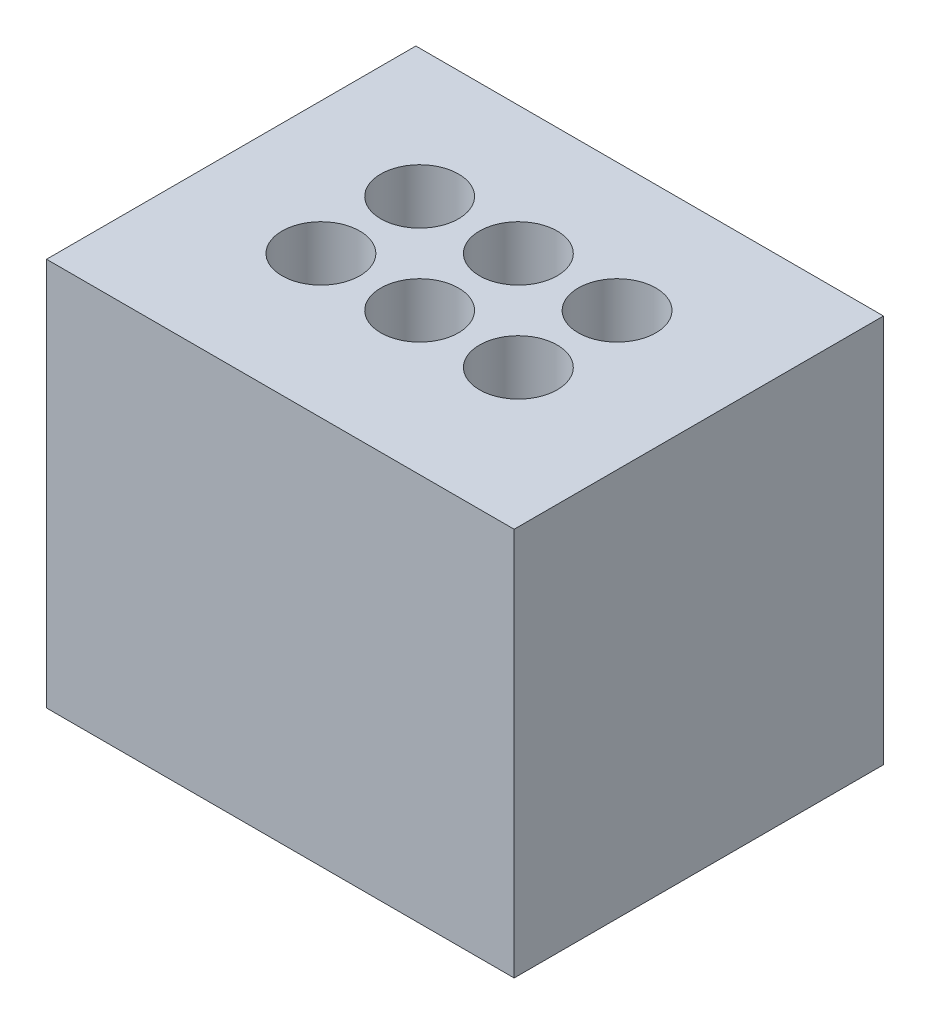
SolidWorks part; units mm, degrees
ref_plane "Front Plane" through (0, 0, 0) normal (0, 0, 1) x (1, 0, 0)
ref_plane "Top Plane" through (0, 0, 0) normal (0, 1, 0) x (1, 0, 0)
ref_plane "Right Plane" through (0, 0, 0) normal (1, 0, 0) x (0, 0, -1)
sketch "Sketch1" plane through (0, 0, 0) normal (0, 1, 0) x (1, 0, 0)
  line L0 (15.2809, 10.3866) -> (15.2809, 12.9266) construction
  line L1 (11.8803, 16.2297) -> (23.9122, 16.2297)
  line L2 (11.8803, 16.2297) -> (11.8803, 6.7266)
  line L3 (11.8803, 6.7266) -> (23.9122, 6.7266)
  line L4 (23.9122, 16.2297) -> (23.9122, 6.7266)
  circle A0 centre (15.2809, 10.3866) radius 1
  circle A1 centre (17.8209, 10.3866) radius 1
  circle A2 centre (20.3609, 10.3866) radius 1
  circle A3 centre (15.2809, 12.9266) radius 1
  circle A4 centre (17.8209, 12.9266) radius 1
  circle A5 centre (20.3609, 12.9266) radius 1
  dimension "D1" = 3
  dimension "D3" = 2.54
  dimension "D2" = 2
extrude "Boss-Extrude1" add sketch "Sketch1" along normal blind 10
